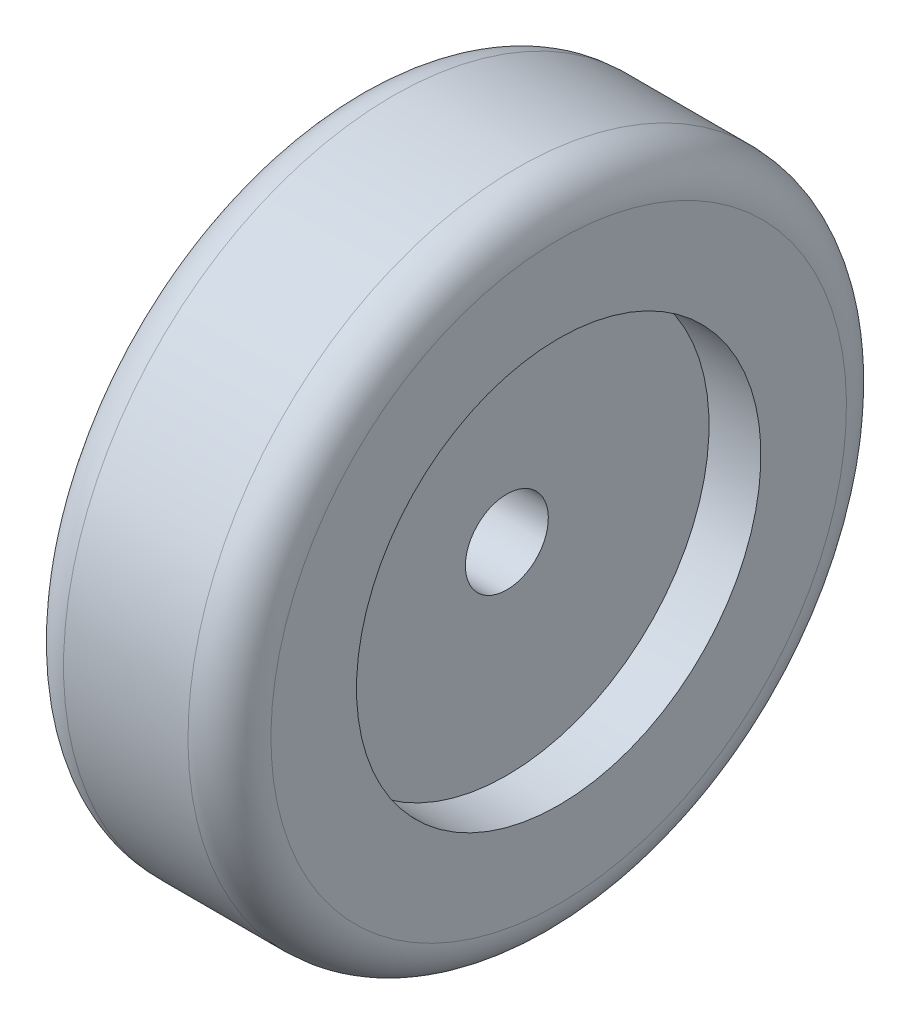
SolidWorks part; units mm, degrees
ref_plane "Alzado" through (0, 0, 0) normal (0, 0, 1) x (1, 0, 0)
ref_plane "Planta" through (0, 0, 0) normal (0, 1, 0) x (1, 0, 0)
ref_plane "Vista lateral" through (0, 0, 0) normal (1, 0, 0) x (0, 0, -1)
sketch "Croquis1" plane through (0, 0, 0) normal (0, 0, 1) x (1, 0, 0)
  line L0 (0, 0) -> (0, 19.5)
  line L1 (0, 19.5) -> (5, 19.5)
  line L2 (5, 19.5) -> (5, 31.75)
  line L3 (5, 31.75) -> (-15, 31.75)
  line L4 (-15, 31.75) -> (-15, 19.5)
  line L5 (-15, 19.5) -> (-18, 10)
  line L6 (-18, 10) -> (-18, 0)
  line L7 (-18, 0) -> (0, 0)
  point P3 (-5, 31.75)
  point P10 (-9, 0)
  dimension "D1" = 31.75
  dimension "D2" = 23
  dimension "D3" = 19.5
  dimension "D4" = 5
  dimension "D5" = 20
  dimension "D6" = 10
revolve "Revolución1" add sketch "Croquis1" angle 360 about L7
sketch "Croquis2" plane through (-18, 0, 0) normal (-1, 0, 0) x (0, 0, 1)
  circle A0 centre (0, 0) radius 4
  dimension "D1" = 8
extrude "Cortar-Extruir1" cut sketch "Croquis2" against normal through all
fillet "Redondeo1" radius 4 2 edges at (-15, -31.75, 0) (5, -31.75, 0)
